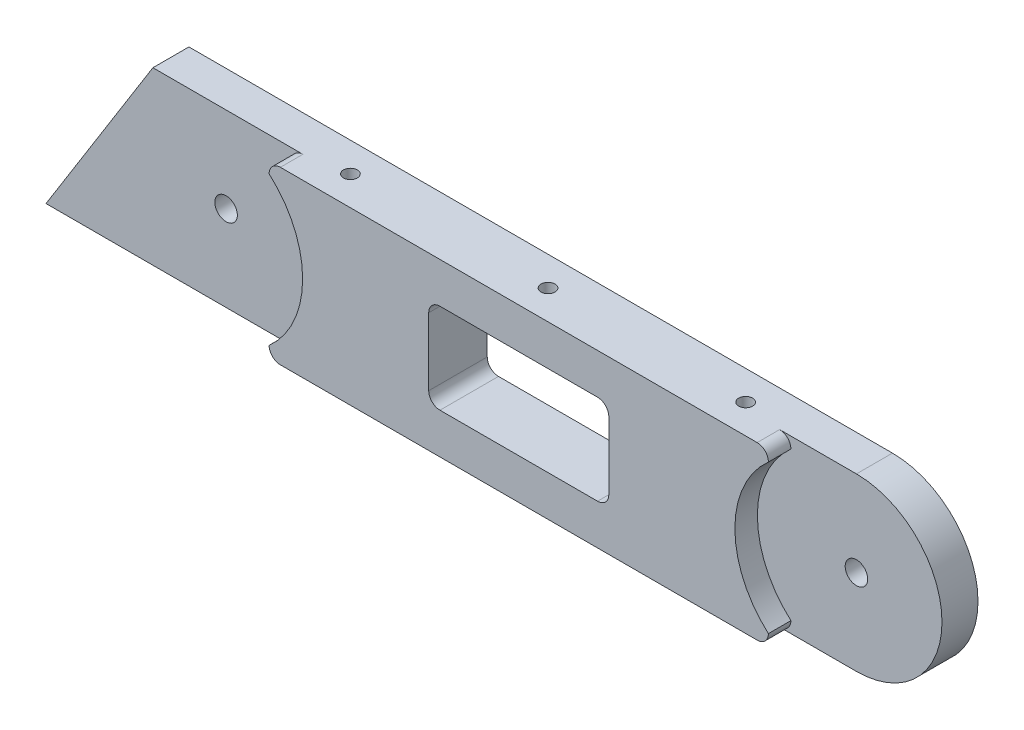
SolidWorks part; units mm, degrees
ref_plane "Front Plane" through (0, 0, 0) normal (0, 0, 1) x (1, 0, 0)
ref_plane "Top Plane" through (0, 0, 0) normal (0, 1, 0) x (1, 0, 0)
ref_plane "Right Plane" through (0, 0, 0) normal (1, 0, 0) x (0, 0, -1)
sketch "Sketch1" plane through (0, 0, 0) normal (0, 0, 1) x (1, 0, 0)
  line L0 (-90, -19) -> (-66.255, 19)
  line L1 (90, -19) -> (-90, -19)
  line L2 (90, -19) -> (90, 19)
  line L3 (90, 19) -> (-66.255, 19)
  line L5 (-66.255, 19) -> (90, -19) construction
  line L6 (90, 19) -> (-90, -19) construction
  line L12 (37.5, -10) -> (2.5, -10)
  line L13 (40, -7.5) -> (40, 7.5)
  line L14 (37.5, 10) -> (2.5, 10)
  line L15 (0, -7.5) -> (0, 7.5)
  line L16 (40, -10) -> (0, 10) construction
  line L17 (40, 10) -> (0, -10) construction
  circle A0 centre (90, 0) radius 19
  circle A1 centre (-50, 0) radius 2.5
  arc A2 (40, 7.5) -> (37.5, 10) centre (37.5, 7.5) ccw
  arc A3 (37.5, -10) -> (40, -7.5) centre (37.5, -7.5) ccw
  arc A4 (2.5, -10) -> (0, -7.5) centre (2.5, -7.5) cw
  arc A5 (2.5, 10) -> (0, 7.5) centre (2.5, 7.5) ccw
  circle A6 centre (90, 0) radius 2.5
  point P0 (0, 0)
  point P10 (0, 0)
  point P11 (20, 0)
  dimension "D3" = 58
  dimension "D6" = 5
  dimension "D12" = 2.5
  dimension "D13" = 5
  dimension "D1" = 180
  dimension "D2" = 38
  dimension "D4" = 2.8055
  dimension "D5" = 40
  dimension "D7" = 19
  dimension "D8" = 29
  dimension "D9" = 9
  dimension "D10" = 110
  dimension "D11" = 90
extrude "Boss-Extrude3" add sketch "Sketch1" along normal blind 8 contours A0 L3 L0 L1 A5 L14 A2 L13 A3 L12 A4 L15 A1 | A6 L2 A0 | A6 L2 A0
sketch "Sketch3" plane through (0, 0, 8) normal (0, 0, 1) x (1, 0, 0)
  line L0 (90, 19) -> (-66.255, 19) construction
  line L1 (-32.9484, 19) -> (72.9484, 19)
  line L2 (-35.4484, 16.5) -> (-35.4484, -16.5)
  line L3 (-32.9484, -19) -> (72.9484, -19)
  line L4 (75.4484, 16.5) -> (75.4484, -16.5)
  line L5 (90, -19) -> (-90, -19) construction
  circle A0 centre (-50, 0) radius 22 construction
  arc A1 (72.9484, -19) -> (75.4484, -16.5) centre (72.9484, -16.5) ccw
  arc A2 (75.4484, 16.5) -> (72.9484, 19) centre (72.9484, 16.5) ccw
  arc A3 (-32.9484, -19) -> (-35.4484, -16.5) centre (-32.9484, -16.5) cw
  arc A4 (-32.9484, 19) -> (-35.4484, 16.5) centre (-32.9484, 16.5) ccw
  circle A5 centre (90, 0) radius 22 construction
  point P13 (75.4484, -19)
  point P20 (-35.4484, 19)
  dimension "D1" = 44
  dimension "D2" = 2.5
  dimension "D3" = 44
sketch "Sketch7" plane through (0, 0, 8) normal (0, 0, 1) x (1, 0, 0)
extrude "Boss-Extrude7" add sketch "Sketch3" along normal blind 5 contours L2 A3 L3 A1 L4 A2 L1 A4
sketch "Sketch14" plane through (0, 0, 13) normal (0, 0, 1) x (1, 0, 0)
  line L1 (2.5, -10) -> (37.5, -10)
  line L2 (0, -7.5) -> (0, 7.5)
  line L3 (2.5, 10) -> (37.5, 10)
  line L4 (40, -7.5) -> (40, 7.5)
  arc A0 (37.5, -10) -> (40, -7.5) centre (37.5, -7.5) ccw
  arc A1 (40, 7.5) -> (37.5, 10) centre (37.5, 7.5) ccw
  arc A2 (2.5, -10) -> (0, -7.5) centre (2.5, -7.5) cw
  arc A3 (2.5, 10) -> (0, 7.5) centre (2.5, 7.5) ccw
  point P9 (40, 10)
  point P12 (0, -10)
  point P15 (0, 10)
  dimension "D3" = 2.5
  dimension "D1" = 40
  dimension "D2" = 20
extrude "Cut-Extrude1" cut sketch "Sketch14" against normal through all contours L2 A3 L3 A1 L4 A0 L1 A2
sketch "Sketch16" plane through (0, 0, 8) normal (0, 0, 1) x (1, 0, 0)
sketch "Sketch18" plane through (0, -19, 0) normal (0, -1, 0) x (1, 0, 0)
  line L0 (-90, 8) -> (-90, 0) construction
  line L1 (90, 0) -> (-90, 0) construction
  circle A0 centre (-23.89, 6.5) radius 1.55
  circle A1 centre (20, 6.5) radius 1.55
  circle A2 centre (63.89, 6.5) radius 1.55
  dimension "D1" = 3.1
  dimension "D4" = 110
  dimension "D5" = 153.89
  dimension "D2" = 66.11
  dimension "D3" = 6.5
extrude "Cut-Extrude2" cut sketch "Sketch18" against normal blind 6
sketch "Sketch19" plane through (0, 19, 0) normal (0, 1, 0) x (1, 0, 0)
  circle A0 centre (-23.89, -6.5) radius 1.55
  circle A1 centre (20, -6.5) radius 1.55
  circle A2 centre (63.89, -6.5) radius 1.55
  dimension "D1" = 3.1
extrude "Cut-Extrude3" cut sketch "Sketch19" against normal blind 6
sketch "Sketch21" plane through (0, 0, 13) normal (0, 0, 1) x (1, 0, 0)
  circle A0 centre (-50, 0) radius 22
  circle A1 centre (90, 0) radius 22
  dimension "D1" = 44
extrude "Cut-Extrude5" cut sketch "Sketch21" against normal blind 5
